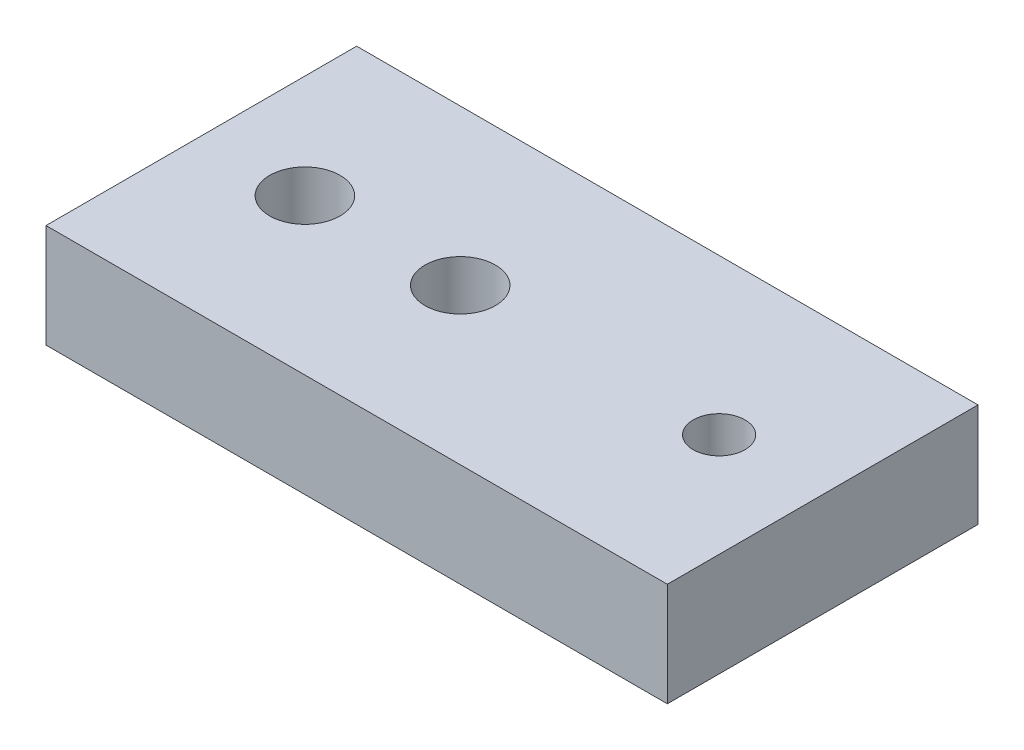
SolidWorks part; units mm, degrees
ref_plane "前视基准面" through (0, 0, 0) normal (0, 0, 1) x (1, 0, 0)
ref_plane "上视基准面" through (0, 0, 0) normal (0, 1, 0) x (1, 0, 0)
ref_plane "右视基准面" through (0, 0, 0) normal (1, 0, 0) x (0, 0, -1)
sketch "草图1" plane through (0, 0, 0) normal (0, 1, 0) x (1, 0, 0)
  line L1 (-30, 15) -> (30, 15)
  line L2 (-30, 15) -> (-30, -15)
  line L3 (-30, -15) -> (30, -15)
  line L4 (30, 15) -> (30, -15)
  line L5 (-30, 15) -> (30, -15) construction
  line L6 (-30, -15) -> (30, 15) construction
  point P0 (0, 0)
  dimension "D1" = 60
  dimension "D2" = 30
extrude "凸台-拉伸1" add sketch "草图1" along normal blind 10
sketch "草图2" plane through (0, 10, 0) normal (0, 1, 0) x (1, 0, 0)
  line L0 (-5, 0) -> (-20, 0)
  line L1 (-30, 15) -> (-30, -15) construction
  line L2 (15, 0) -> (20, 0)
  line L3 (30, -15) -> (30, 15) construction
  dimension "D1" = 15
  dimension "D2" = 10
  dimension "D3" = 10
  dimension "D4" = 5
hole_wizard "大小mm 暗销孔1" positions "3D草图1" profile "草图3" hole size "Ø1.0" standard "GB" end condition through all
sketch3d "3D草图1"
  point P0 (-20, 10, 0)
  point P3 (-5, 10, 0)
sketch "草图3" plane through (-20, 10, 0) normal (1, 0, 0) x (0, 0, 1)
  line L0 (0, 0) -> (0, 10)
  line L1 (0, 10) -> (3.4, 10)
  line L2 (3.4, 10) -> (3.4, 0)
  line L5 (3.4, 0) -> (0, 0)
  line L11 (0, -6.35) -> (0, 107.95) construction
  dimension "通孔孔直径" = 6.8
  dimension "通孔孔深度" = 10
hole_wizard "M6 螺纹孔1" positions "3D草图2" profile "草图4" tap size "M6" standard "GB" end condition through all
sketch3d "3D草图2"
  point P0 (20, 10, 0)
sketch "草图4" plane through (20, 10, 0) normal (1, 0, 0) x (0, 0, 1)
  line L0 (0, 0) -> (0, 10)
  line L1 (0, 10) -> (2.5, 10)
  line L2 (2.5, 10) -> (2.5, 0)
  line L5 (2.5, 0) -> (0, 0)
  line L11 (0, -6.35) -> (0, 107.95) construction
  dimension "通孔螺纹孔钻头直径" = 5
  dimension "通孔螺纹孔钻头深度" = 10
cosmetic thread "孔螺蚊线1"
